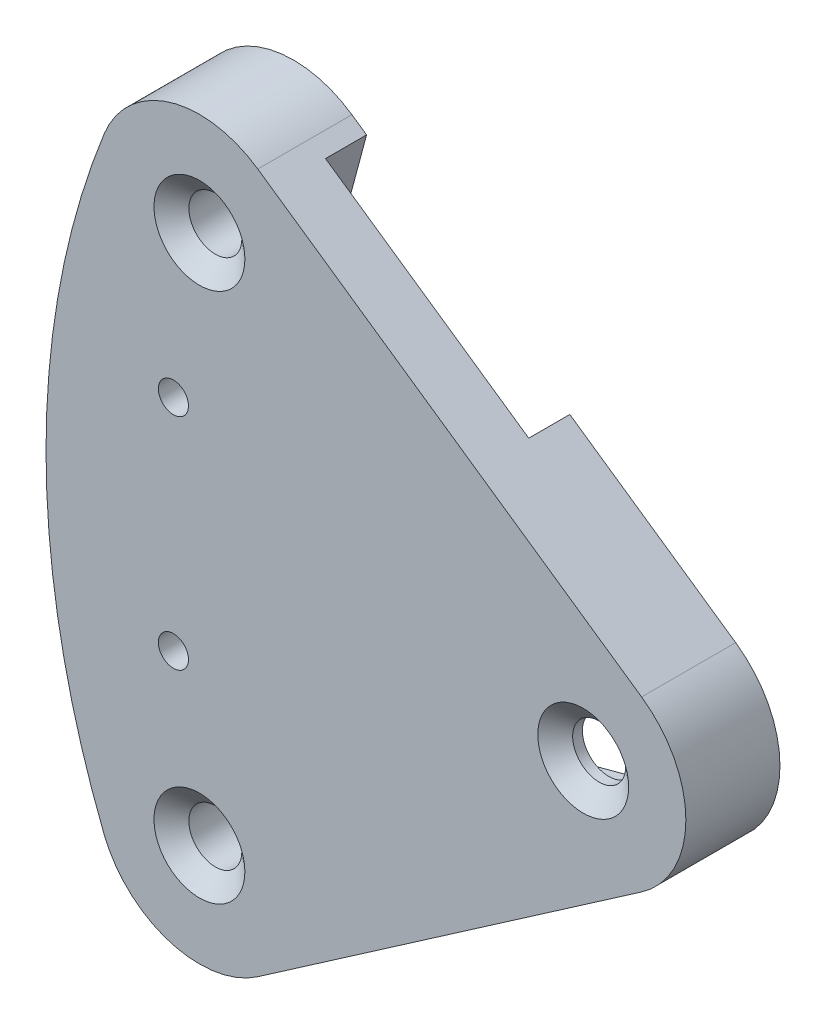
SolidWorks part; units mm, degrees
material "PET"
ref_plane "Front Plane" through (0, 0, 0) normal (0, 0, 1) x (1, 0, 0)
ref_plane "Top Plane" through (0, 0, 0) normal (0, 1, 0) x (1, 0, 0)
ref_plane "Right Plane" through (0, 0, 0) normal (1, 0, 0) x (0, 0, -1)
sketch "Sketch1" plane through (0, 0, 0) normal (0, 0, 1) x (1, 0, 0)
  line L0 (-33.2997, 0) -> (33.2997, 0) construction
  line L1 (33.2997, 0) -> (-33.2997, 46.0375)
  line L2 (-33.2997, 46.0375) -> (-33.2997, -46.0375)
  line L3 (33.2997, 0) -> (-33.2997, -46.0375)
  point P4 (0, 0)
  dimension "D1" = 80.9625
  dimension "D2" = 46.0375
extrude "Boss-Extrude1" add sketch "Sketch1" along normal blind 8.7312
sketch "Sketch2" plane through (0, 0, 8.7312) normal (0, 0, 1) x (1, 0, 0)
  line L0 (-33.2997, 0) -> (33.2997, 0) construction
  line L1 (-33.2997, 46.0375) -> (-33.2997, -46.0375) construction
  circle A0 centre (42.9003, 0) radius 76.2
  circle A2 centre (42.9003, 0) radius 101.6
  dimension "D1" = 152.4
  dimension "D2" = 25.4
extrude "Cut-Extrude1" cut sketch "Sketch2" against normal through all
fillet "Fillet1" radius 9.525 3 edges at (-22.7246, 38.7274, 4.3656) (33.2997, 0, 4.3656) (-22.7246, -38.7274, 4.3656)
hole_wizard "CSK for #8 Flat Head Machine Screw (100)1" positions "Sketch3" profile "Sketch4" countersink size "#8" standard "ANSI Inch" end condition up to next
sketch "Sketch3" plane through (0, 0, 8.7312) normal (0, 0, 1) x (1, 0, 0)
  point P0 (-19.0637, -24.6175)
  point P2 (-19.0637, 24.6175)
  point P4 (16.5488, 0)
sketch "Sketch4" plane through (-19.0637, -24.6175, 8.7312) normal (1, 0, 0) x (0, -1, 0)
  line L0 (0, 0) -> (0, 8.7312)
  line L1 (0, 8.7312) -> (2.4574, 8.7312)
  line L2 (2.4574, 8.7312) -> (2.4574, 1.4759)
  line L3 (2.4574, 1.4759) -> (4.2164, 0)
  line L5 (4.2164, 0) -> (0, 0)
  line L6 (-2.4574, 1.4759) -> (-4.2164, 0) construction
  line L11 (0, -6.35) -> (0, 107.95) construction
  dimension "Thru Hole Dia." = 4.9149
  dimension "Thru Hole Depth" = 8.7312
  dimension "Near C'Sink Dia." = 8.4328
  dimension "Near C'Sink Angle" = 100
sketch "Sketch5" plane through (0, 0, 0) normal (0, 0, -1) x (-1, 0, 0)
  line L0 (33.2997, 0) -> (-16.5488, 0) construction
  line L1 (30.8235, 19.2674) -> (-18.1923, 6.1336)
  line L2 (-16.5488, 0) -> (-22.8988, 0) construction
  line L3 (30.8235, -19.2674) -> (-18.1923, -6.1336)
  arc A0 (-18.1923, 6.1336) -> (-18.1923, -6.1336) centre (-16.5488, 0) ccw
  arc A1 (27.9157, -28.1343) -> (27.9157, 28.1343) centre (-42.9003, 0) ccw construction
  arc A2 (30.8235, -19.2674) -> (30.8235, 19.2674) centre (-42.9003, 0) ccw
  dimension "D1" = 12.7
  dimension "D2" = 15
extrude "Cut-Extrude2" cut sketch "Sketch5" against normal blind 6.35
sketch "Sketch6" plane through (0, 0, 0) normal (0, 0, -1) x (-1, 0, 0)
  line L0 (16.5887, -15.4532) -> (-4.2656, -9.8653)
  line L1 (16.5887, -15.4532) -> (11.9869, -32.6273)
  line L2 (-4.2656, -9.8653) -> (-8.8674, -27.0394)
  line L3 (11.9869, -32.6273) -> (-8.8674, -27.0394)
  line L4 (-18.1923, -6.1336) -> (30.8235, -19.2674) construction
  line L5 (33.2997, 0) -> (-26.0738, 0) construction
  line L6 (11.9869, 32.6273) -> (-8.8674, 27.0394)
  line L7 (-4.2656, 9.8653) -> (-8.8674, 27.0394)
  line L8 (16.5887, 15.4532) -> (11.9869, 32.6273)
  line L9 (16.5887, 15.4532) -> (-4.2656, 9.8653)
  arc A1 (30.8235, -19.2674) -> (30.8235, 19.2674) centre (-42.9003, 0) ccw construction
  arc A2 (-21.965, 7.8352) -> (-21.965, -7.8352) centre (-16.5488, 0) ccw construction
  dimension "D2" = 21.59
  dimension "D3" = 17.78
extrude "Cut-Extrude3" cut sketch "Sketch6" against normal blind 3.81
sketch "Sketch7" plane through (0, 0, 6.35) normal (0, 0, -1) x (-1, 0, 0)
  line L0 (33.2997, 0) -> (0, 0) construction
  circle A0 centre (21.4797, -10.1897) radius 1.397
  arc A1 (30.8235, -19.2674) -> (30.8235, 19.2674) centre (-42.9003, 0) ccw construction
  circle A2 centre (21.4797, 10.1897) radius 1.397
  dimension "D1" = 2.794
extrude "Cut-Extrude4" cut sketch "Sketch7" against normal blind 3.175
hole_wizard "Hole1" positions "Sketch8" profile "Sketch9" legacy
sketch "Sketch8" plane through (0, 0, 3.81) normal (0, 0, -1) x (-1, 0, 0)
  line L0 (0, 0) -> (-16.5488, 0) construction
  point P0 (8.9047, -20.0866)
  point P3 (-0.1363, -17.6641)
  point P12 (-0.1363, 17.6641)
  point P13 (8.9047, 20.0866)
sketch "Sketch9" plane through (-8.9047, -20.0866, 3.81) normal (1, 0, 0) x (0, 1, 0)
  line L0 (0, 0) -> (0, 2.921)
  line L1 (0, 2.921) -> (1.4986, 2.921)
  line L2 (1.4986, 2.921) -> (1.6383, 0)
  line L3 (1.6383, 0) -> (0, 0)
  line L4 (0, 110) -> (0, -10) construction
  dimension "Minor Diameter" = 2.9972
  dimension "Depth" = 2.921
  dimension "Major Diameter" = 3.2766
hole_wizard "#2 Clearance Hole1" positions "Sketch10" profile "Sketch11" hole size "#2" standard "ANSI Inch"
sketch "Sketch10" plane through (0, 0, 3.81) normal (0, 0, -1) x (-1, 0, 0)
  line L0 (0, 0) -> (-42.9003, 0) construction
  point P0 (8.9047, -20.0866)
  point P3 (-0.1363, -17.6641)
  point P17 (-0.1363, 17.6641)
  point P18 (8.9047, 20.0866)
sketch "Sketch11" plane through (-8.9047, -20.0866, 3.81) normal (1, 0, 0) x (0, 1, 0)
  line L0 (0, 0) -> (0, 4.7625)
  line L1 (0, 4.7625) -> (1.3525, 4.7625)
  line L2 (1.3525, 4.7625) -> (1.3525, 0)
  line L5 (1.3525, 0) -> (0, 0)
  line L10 (0, 4.7625) -> (-1.3526, 4.7625) construction
  line L11 (0, -6.35) -> (0, 107.95) construction
  dimension "Hole Dia." = 2.7051
  dimension "Hole Depth" = 4.7625
  dimension "Drill Angle" = 180
